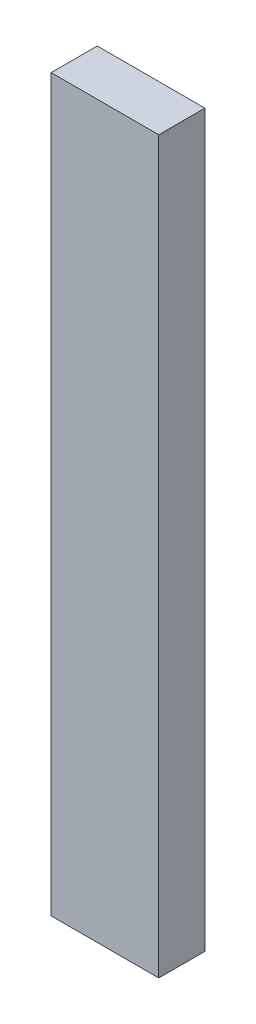
SolidWorks part; units mm, degrees
ref_plane "Front Plane" through (0, 0, 0) normal (0, 0, 1) x (1, 0, 0)
ref_plane "Top Plane" through (0, 0, 0) normal (0, 1, 0) x (1, 0, 0)
ref_plane "Right Plane" through (0, 0, 0) normal (1, 0, 0) x (0, 0, -1)
sketch "Sketch1" plane through (0, 0, 0) normal (0, 1, 0) x (1, 0, 0)
  line L1 (-44.45, -19.05) -> (44.45, -19.05)
  line L2 (-44.45, -19.05) -> (-44.45, 19.05)
  line L3 (-44.45, 19.05) -> (44.45, 19.05)
  line L4 (44.45, -19.05) -> (44.45, 19.05)
  line L5 (-44.45, -19.05) -> (44.45, 19.05) construction
  line L6 (-44.45, 19.05) -> (44.45, -19.05) construction
  point P0 (0, 0)
  dimension "D1" = 88.9
  dimension "D2" = 38.1
extrude "Boss-Extrude1" add sketch "Sketch1" along normal blind 603.25
